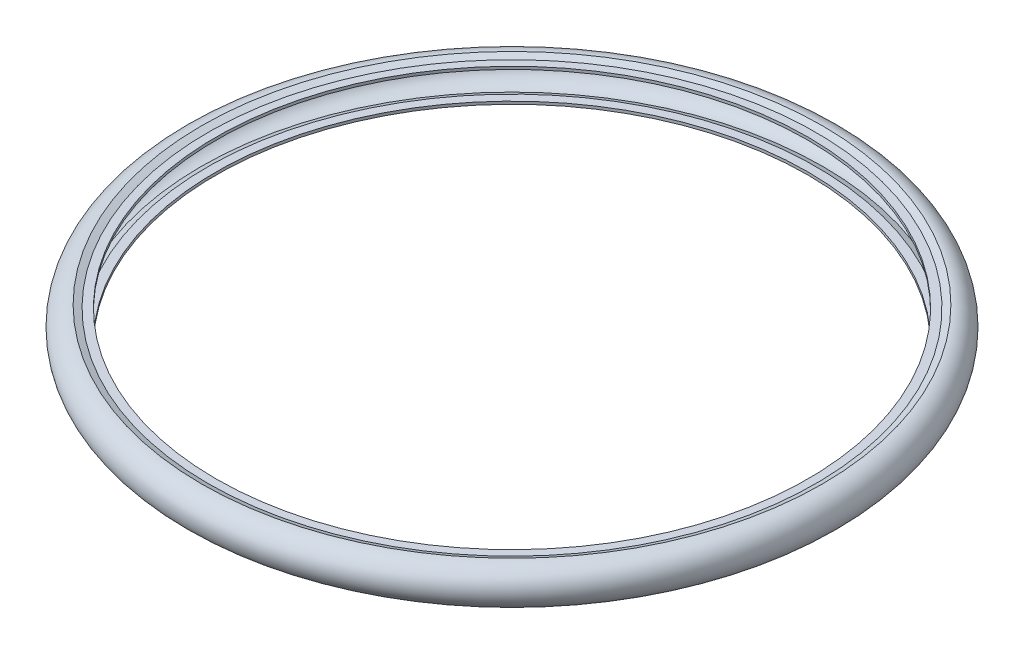
SolidWorks part; units mm, degrees
material "BUTYL"
ref_plane "Front Plane" through (0, 0, 0) normal (0, 0, 1) x (1, 0, 0)
ref_plane "Top Plane" through (0, 0, 0) normal (0, 1, 0) x (1, 0, 0)
ref_plane "Right Plane" through (0, 0, 0) normal (1, 0, 0) x (0, 0, -1)
sketch "Sketch1" plane through (0, 0, 0) normal (1, 0, 0) x (0, 0, -1)
  line L0 (0, 0) -> (240, 0) construction
  line L8 (0, 21.8974) -> (0, -17.9858) construction
  line L10 (217.5946, -10) -> (215.5946, -10)
  line L11 (217.5946, 10) -> (215.5946, 10)
  line L16 (215.5946, -12) -> (221.4373, -12)
  line L17 (217.5946, 10) -> (221.8468, 10)
  line L20 (215.5946, -10) -> (215.5946, -12)
  line L21 (217.5946, -10) -> (221.8468, -10)
  line L22 (221.4373, 12) -> (226.035, 13.965)
  line L23 (221.8468, -10) -> (226.4293, -11.9585)
  line L24 (215.5946, 10) -> (215.5946, 12)
  line L25 (221.4373, -12) -> (226.035, -13.965)
  line L26 (221.8468, 10) -> (226.4293, 11.9585)
  line L27 (215.5946, 12) -> (221.4373, 12)
  arc A1 (226.035, 13.965) -> (226.035, -13.965) centre (226.035, 0) cw
  arc A3 (226.4293, 11.9585) -> (226.4293, -11.9585) centre (226.035, 0) cw
  dimension "D4" = 5
  dimension "D1" = 240
revolve "Revolve1" add sketch "Sketch1" angle 360 about L8
ref_plane "Plane1" through (0, 0, 240) normal (0, 0, 1) x (1, 0, 0)
